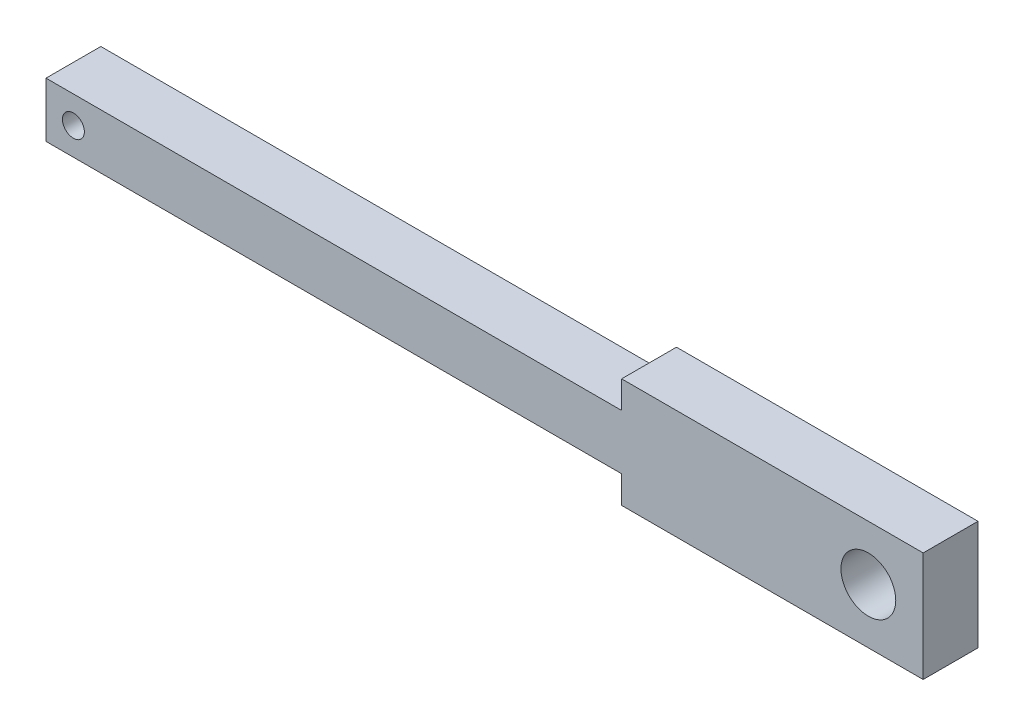
SolidWorks part; units mm, degrees
ref_plane "前视基准面" through (0, 0, 0) normal (0, 0, 1) x (1, 0, 0)
ref_plane "上视基准面" through (0, 0, 0) normal (0, 1, 0) x (1, 0, 0)
ref_plane "右视基准面" through (0, 0, 0) normal (1, 0, 0) x (0, 0, -1)
sketch "草图1" plane through (0, 0, 0) normal (0, 0, 1) x (1, 0, 0)
  line L0 (0, -5) -> (5, -5) construction
  line L1 (0, 0) -> (105, 0)
  line L2 (0, 0) -> (0, -10)
  line L3 (0, -10) -> (105, -10)
  line L5 (155, -5) -> (102.8125, -5) construction
  line L6 (77.5, -10) -> (77.5, 20.8229) construction
  line L8 (155, 0) -> (155, 5)
  line L9 (155, 5) -> (105, 5)
  line L10 (105, 0) -> (105, 5)
  line L11 (155, -15) -> (105, -15)
  line L12 (105, -10) -> (105, -15)
  line L16 (155, 5) -> (160, 5)
  line L17 (155, 5) -> (155, -5)
  line L18 (155, -15) -> (160, -15)
  line L19 (160, 5) -> (160, -15)
  circle A2 centre (150, -5) radius 5
  circle A3 centre (5, -5) radius 2
  dimension "D7" = 10
  dimension "D8" = 4
  dimension "D1" = 155
  dimension "D2" = 10
  dimension "D3" = 145
  dimension "D4" = 5
  dimension "D5" = 50
  dimension "D6" = 5
extrude "凸台-拉伸1" add sketch "草图1" along normal blind 10
